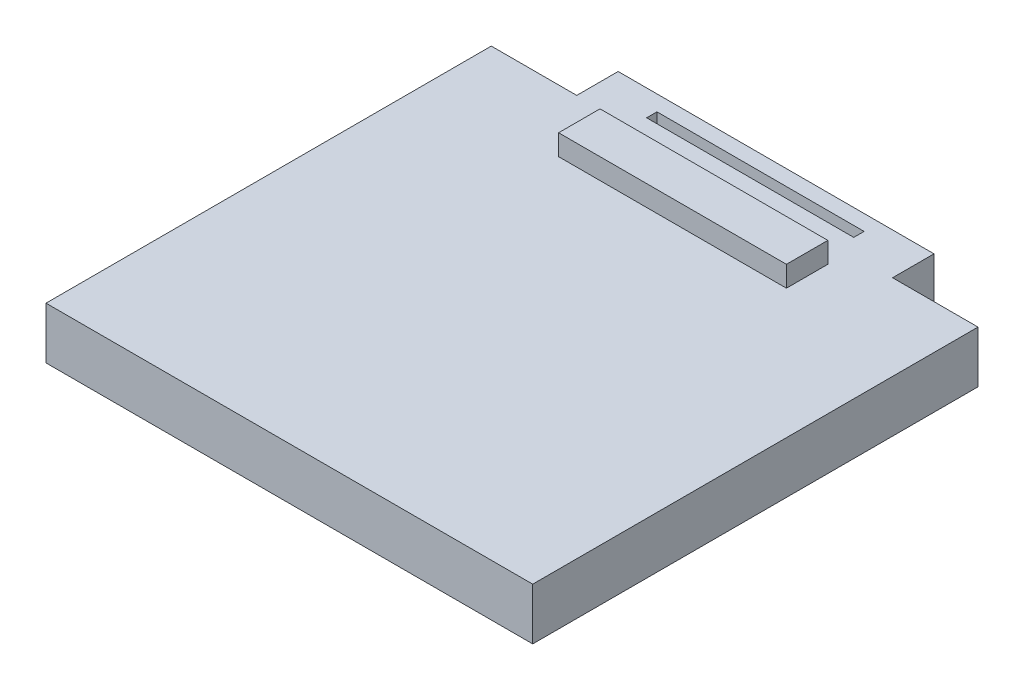
SolidWorks part; units mm, degrees
ref_plane "Alzado" through (0, 0, 0) normal (0, 0, 1) x (1, 0, 0)
ref_plane "Planta" through (0, 0, 0) normal (0, 1, 0) x (1, 0, 0)
ref_plane "Vista lateral" through (0, 0, 0) normal (1, 0, 0) x (0, 0, -1)
sketch "Croquis1" plane through (0, 0, 0) normal (0, 1, 0) x (1, 0, 0)
  line L1 (-11.75, 10.75) -> (11.75, 10.75)
  line L2 (-11.75, 10.75) -> (-11.75, -10.75)
  line L3 (-11.75, -10.75) -> (11.75, -10.75)
  line L4 (11.75, 10.75) -> (11.75, -10.75)
  line L5 (-11.75, 10.75) -> (11.75, -10.75) construction
  line L6 (-11.75, -10.75) -> (11.75, 10.75) construction
  point P0 (0, 0)
  dimension "D1" = 23.5
  dimension "D2" = 21.5
extrude "Saliente-Extruir1" add sketch "Croquis1" along normal blind 2.5
sketch "Croquis2" plane through (0, 0, -10.75) normal (0, 0, -1) x (-1, 0, 0)
  line L0 (-7.625, 2.5) -> (-7.625, 0)
  line L1 (-11.75, 2.5) -> (11.75, 2.5) construction
  line L2 (-11.75, 0) -> (11.75, 0) construction
  line L3 (-7.625, 0) -> (7.625, 0)
  line L4 (7.625, 0) -> (7.625, 2.5)
  line L5 (7.625, 2.5) -> (-7.625, 2.5)
  point P6 (0, 0)
  dimension "D1" = 15.25
extrude "Saliente-Extruir2" add sketch "Croquis2" along normal blind 2
sketch "Croquis4" plane through (0, 2.5, 0) normal (0, 1, 0) x (1, 0, 0)
  line L0 (-7.625, 10.75) -> (-11.75, 10.75) construction
  line L1 (-5.5, 9.75) -> (5.5, 9.75)
  line L2 (-5.5, 9.75) -> (-5.5, 7.75)
  line L3 (-5.5, 7.75) -> (5.5, 7.75)
  line L4 (5.5, 9.75) -> (5.5, 7.75)
  line L5 (-5.5, 9.75) -> (5.5, 7.75) construction
  line L6 (-5.5, 7.75) -> (5.5, 9.75) construction
  point P0 (0, 8.75)
  dimension "D1" = 11
  dimension "D2" = 1
  dimension "D3" = 2
extrude "Saliente-Extruir4" add sketch "Croquis4" along normal blind 1
sketch "Croquis5" plane through (0, 2.5, 0) normal (0, 1, 0) x (1, 0, 0)
  line L0 (-7.625, 12.75) -> (-7.625, 10.75) construction
  line L1 (-5, 12) -> (5, 12)
  line L2 (-5, 12) -> (-5, 11.5)
  line L3 (-5, 11.5) -> (5, 11.5)
  line L4 (5, 12) -> (5, 11.5)
  line L5 (-5, 12) -> (5, 11.5) construction
  line L6 (-5, 11.5) -> (5, 12) construction
  point P0 (0, 11.75)
  point P7 (-7.625, 11.75)
  dimension "D1" = 0.5
  dimension "D2" = 10
extrude "Cortar-Extruir1" cut sketch "Croquis5" against normal blind 0.75
